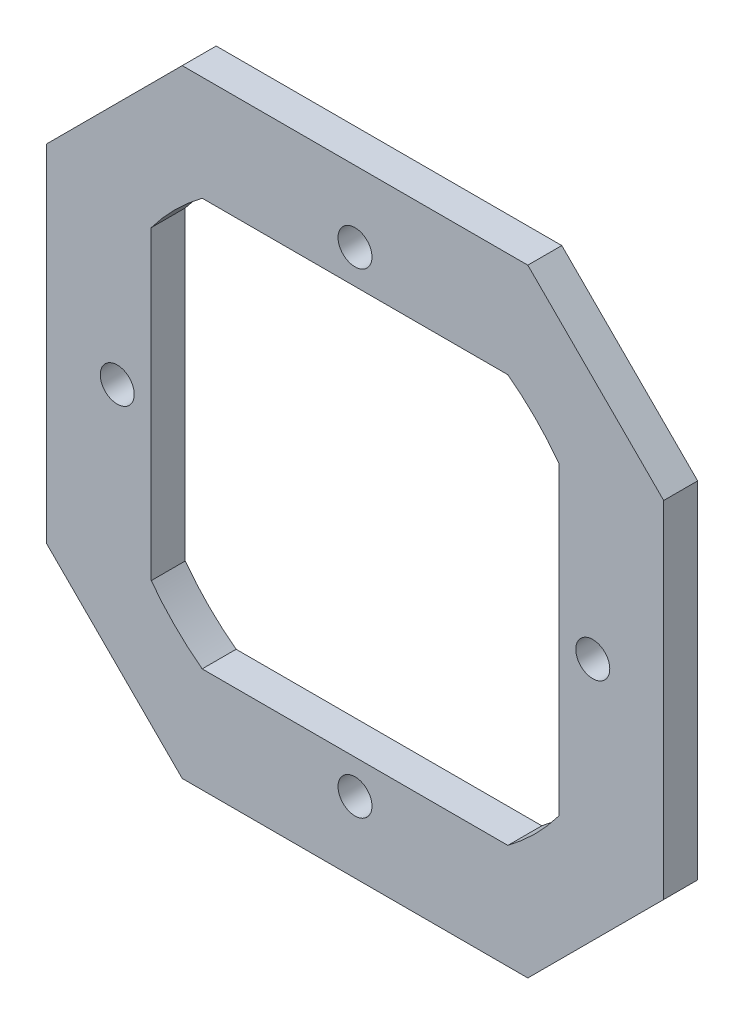
SolidWorks part; units mm, degrees
ref_plane "前视基准面" through (0, 0, 0) normal (0, 0, 1) x (1, 0, 0)
ref_plane "上视基准面" through (0, 0, 0) normal (0, 1, 0) x (1, 0, 0)
ref_plane "右视基准面" through (0, 0, 0) normal (1, 0, 0) x (0, 0, -1)
sketch "草图1" plane through (0, 0, 0) normal (0, 0, 1) x (1, 0, 0)
  line L0 (-18.175, 10.175) -> (-10.175, 18.175)
  line L1 (-9, 12) -> (9, 12)
  line L2 (-12, 9) -> (-12, -9)
  line L3 (-9, -12) -> (9, -12)
  line L4 (12, 9) -> (12, -9)
  line L5 (-12, 12) -> (12, -12) construction
  line L6 (-12, -12) -> (12, 12) construction
  line L7 (-10.175, 18.175) -> (10.175, 18.175)
  line L8 (-18.175, 10.175) -> (-18.175, -10.175)
  line L9 (-10.175, -18.175) -> (10.175, -18.175)
  line L10 (18.175, 10.175) -> (18.175, -10.175)
  line L11 (-18.175, 18.175) -> (18.175, -18.175) construction
  line L12 (-18.175, -18.175) -> (18.175, 18.175) construction
  line L13 (10.175, 18.175) -> (18.175, 10.175)
  line L14 (10.175, -18.175) -> (18.175, -10.175)
  line L15 (-18.175, -10.175) -> (-10.175, -18.175)
  arc A0 (-9, 12) -> (-12, 9) centre (0, 0) ccw
  arc A1 (9, -12) -> (12, -9) centre (0, 0) ccw
  arc A2 (-12, -9) -> (-9, -12) centre (0, 0) ccw
  arc A3 (12, 9) -> (9, 12) centre (0, 0) ccw
  circle A4 centre (0, 14) radius 1
  circle A5 centre (14, 0) radius 1
  circle A6 centre (-14, 0) radius 1
  circle A7 centre (0, -14) radius 1
  point P0 (0, 0)
  point P5 (0, 0)
  dimension "D5" = 30
  dimension "D6" = 28
  dimension "D10" = 2
  dimension "D1" = 36.35
  dimension "D2" = 36.35
  dimension "D3" = 24
  dimension "D4" = 24
  dimension "D7" = 14
  dimension "D8" = 28
  dimension "D9" = 14
extrude "凸台-拉伸1" add sketch "草图1" along normal blind 2
